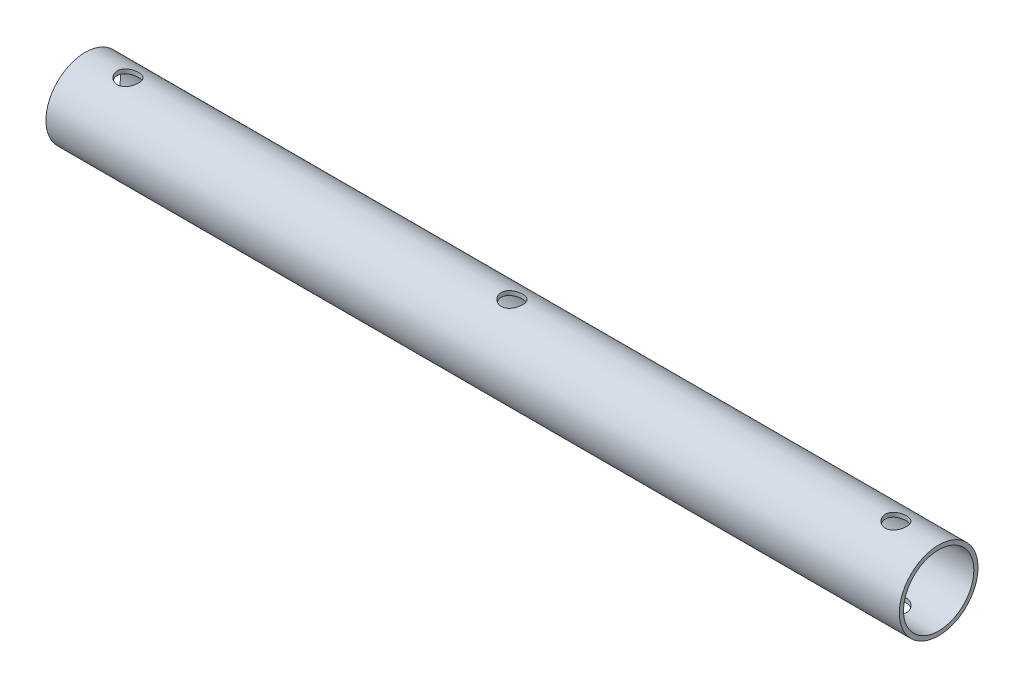
SolidWorks part; units mm, degrees
material "Galvanized Steel"
ref_plane "Front Plane" through (0, 0, 0) normal (0, 0, 1) x (1, 0, 0)
ref_plane "Top Plane" through (0, 0, 0) normal (0, 1, 0) x (1, 0, 0)
ref_plane "Right Plane" through (0, 0, 0) normal (1, 0, 0) x (0, 0, -1)
sketch "Sketch3" plane through (0, 0, 0) normal (1, 0, 0) x (0, 0, -1)
  circle A0 centre (0, 0) radius 10.4648
  circle A1 centre (0, 0) radius 11.7094
  dimension "D1" = 20.9296
  dimension "D2" = 23.4188
extrude "Boss-Extrude1" add sketch "Sketch3" along normal blind 254
sketch "Sketch4" plane through (0, 0, 0) normal (0, 1, 0) x (1, 0, 0)
  line L0 (254, -11.7094) -> (254, 11.7094) construction
  line L1 (0, 11.7094) -> (0, -11.7094) construction
  circle A0 centre (127, 0) radius 3.175
  circle A1 centre (12.7, 0) radius 3.175
  circle A4 centre (241.3, 0) radius 3.175
  dimension "D1" = 6.35
  dimension "D3" = 6.35
  dimension "D5" = 6.35
  dimension "D6" = 127
  dimension "D7" = 12.7
  dimension "D8" = 12.7
extrude "Cut-Extrude1" cut sketch "Sketch4" along normal through all and the other way through all
